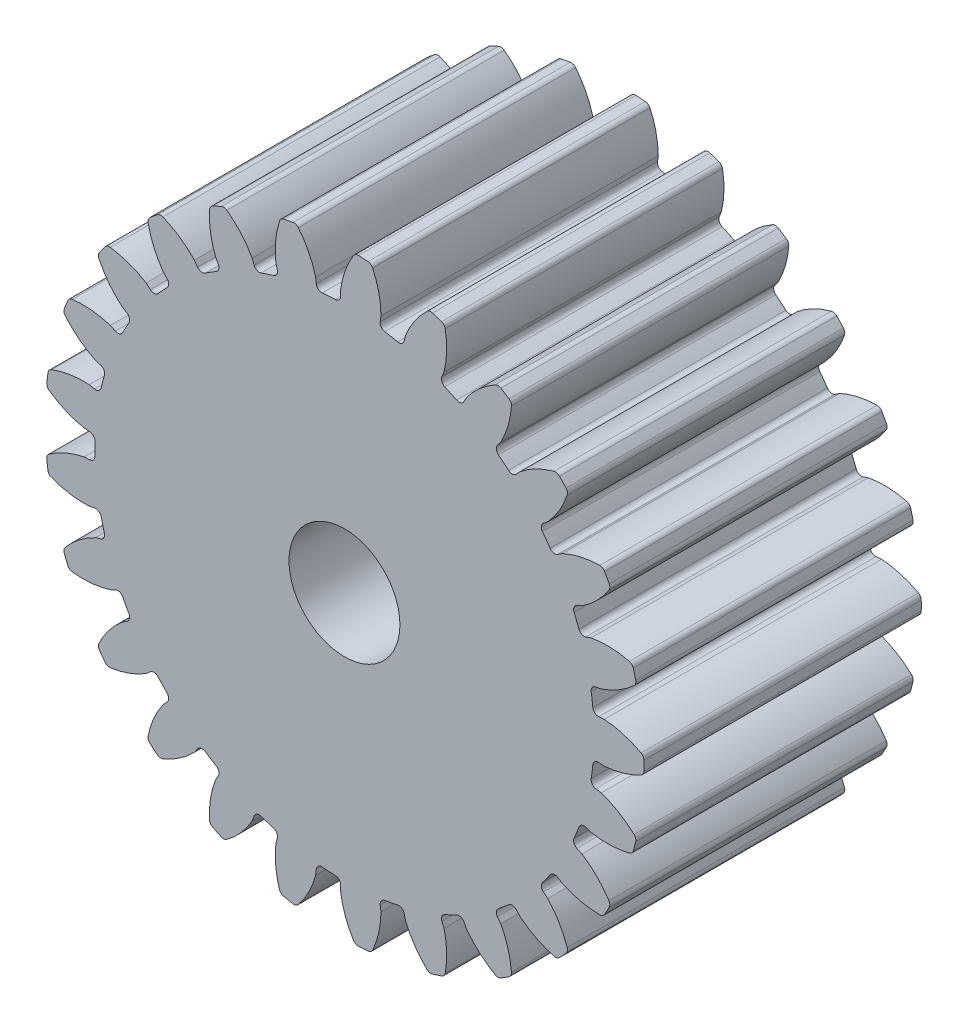
SolidWorks part; units mm, degrees
material "Нержавеющая сталь (ферритная)"
ref_plane "Спереди" through (0, 0, 0) normal (0, 0, 1) x (1, 0, 0)
ref_plane "Сверху" through (0, 0, 0) normal (0, 1, 0) x (1, 0, 0)
ref_plane "Справа" through (0, 0, 0) normal (1, 0, 0) x (0, 0, -1)
sketch "Эскиз1" plane through (0, 0, 0) normal (0, 0, 1) x (1, 0, 0)
  circle A0 centre (0, 0) radius 4.5
  circle A1 centre (0, 0) radius 1
  dimension "D1" = 9
  dimension "D2" = 2
extrude "Бобышка-Вытянуть1" add sketch "Эскиз1" along normal mid plane 5
sketch "Эскиз2" plane through (0, 0, 0) normal (0, 0, 1) x (1, 0, 0)
  line L0 (0, 0) -> (0, 5) construction
  line L1 (0, 5) -> (0.6183, 5) construction
  line L2 (0, 5) -> (1.607, 4.4151) construction
  line L3 (2.4622, 4.0016) -> (0.1953, 5.3965) construction
  line L4 (0, 0) -> (-0.07, 4.6979) construction
  line L5 (-0.07, 4.6979) -> (-0.0671, 4.4995)
  line L6 (0, 0) -> (0.3391, 5.3893) construction
  line L7 (0.6583, 4.6521) -> (0.6305, 4.4556)
  arc A0 (0.4826, 5.3784) -> (0.1953, 5.3965) centre (0, 0) ccw
  circle A1 centre (0, 0) radius 5 construction
  circle A2 centre (0, 0) radius 4.5 construction
  arc A3 (0.6305, 4.4556) -> (-0.0671, 4.4995) centre (0, 0) ccw
  circle A4 centre (0, 0) radius 4.6985 construction
  spline S0 degree 2 poles (-0.07, 4.6979) (-0.0186, 5.0762) (0.1953, 5.3965) knots 0 0 0 1 1 1
  spline S1 degree 2 poles (0.6583, 4.6521) (0.6547, 5.0338) (0.4826, 5.3784) knots 0 0 0 1 1 1
  point P10 (1.607, 4.4151)
  point P11 (-0.07, 4.6979)
  dimension "D1" = 10
  dimension "D2" = 10.8
  dimension "D3" = 20
  dimension "D4" = 1.7101
  dimension "D6" = 2.6617
  dimension "D8" = 3.6
  dimension "D5" = 1.7101
  dimension "D7" = 0.9516
extrude "Бобышка-Вытянуть2" add sketch "Эскиз2" along normal up to surface and the other way up to surface up to face at (4.5, 0, 2.5) other way up to face at (4.5, 0, -2.5)
fillet "Скругление1" radius 0.1 4 edges at (-0.0671, 4.4995, 0) (0.6305, 4.4556, 0) (0.4826, 5.3784, 0) (0.1953, 5.3965, 0)
pattern_circular "Круговой массив1" count 25 over 360 about axis through (0, 0, 2.5) along (0, 0, -1) of "Бобышка-Вытянуть2", "Скругление1"
equation "\"Число зубьев\"= 25"
equation "\"Модуль\"= 0.4мм"
equation "\"D1@Эскиз1\"= \"Модуль\" * (\"Число зубьев\" - 2.5)"
equation "\"D1@Эскиз2\"= \"Модуль\" * \"Число зубьев\""
equation "\"D5@Эскиз2\"= \"D4@Эскиз2\""
equation "\"D7@Эскиз2\"= \"D6@Эскиз2\" - \"D4@Эскиз2\""
equation "\"D8@Эскиз2\"= 90 / \"Число зубьев\""
equation "\"D1@Круговой массив1\"= \"Число зубьев\""
equation "\"D2@Эскиз2\"= \"Модуль\" * (\"Число зубьев\" + 2)"
